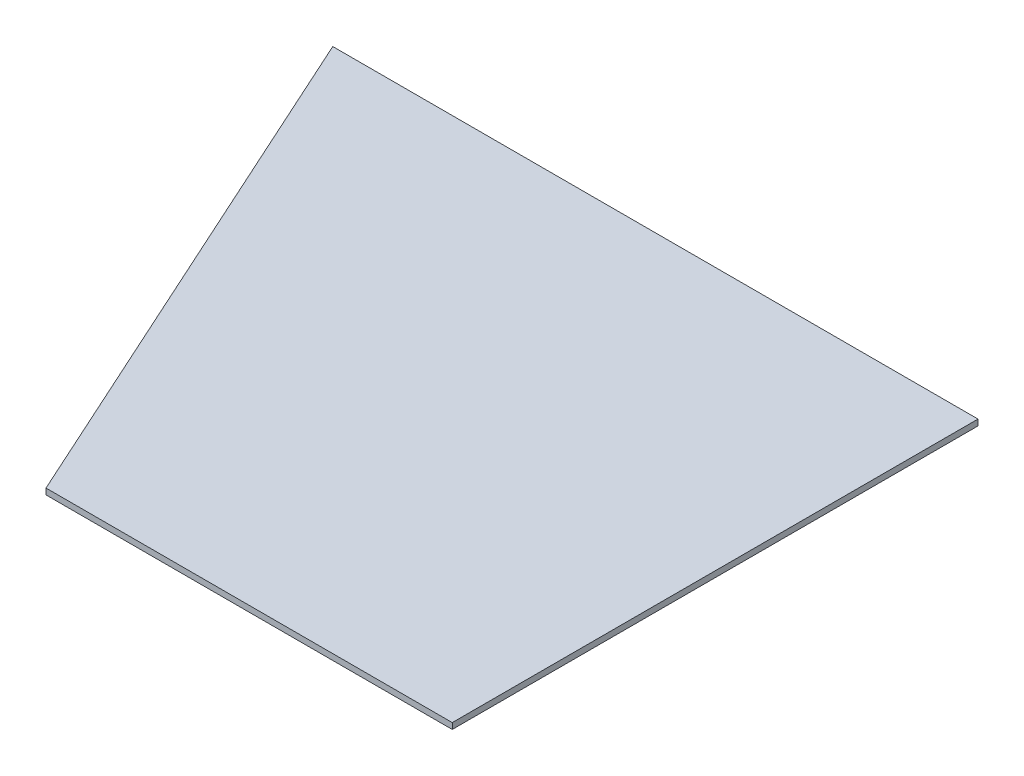
SolidWorks part; units mm, degrees
ref_plane "Front Plane" through (0, 0, 0) normal (0, 0, 1) x (1, 0, 0)
ref_plane "Top Plane" through (0, 0, 0) normal (0, 1, 0) x (1, 0, 0)
ref_plane "Right Plane" through (0, 0, 0) normal (1, 0, 0) x (0, 0, -1)
sketch "Sketch1" plane through (0, 0, 0) normal (0, 1, 0) x (1, 0, 0)
  line L0 (500, 0) -> (716, 0)
  line L1 (716, 0) -> (716, -176)
  line L2 (716, -176) -> (580, -176)
  line L3 (580, -176) -> (500, 0)
  line L4 (0, 0) -> (500, 0) construction
  dimension "D1" = 216
  dimension "D2" = 176
  dimension "D3" = 136
  dimension "D4" = 500
extrude "Boss-Extrude1" add sketch "Sketch1" along normal mid plane 2
chamfer "Chamfer1" [suppressed] distance 1.76 distance2 1
chamfer "Chamfer2" [suppressed] distance 1 distance2 1.76
